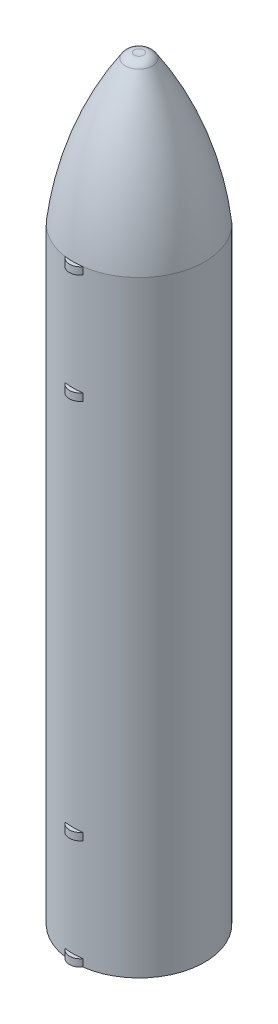
SolidWorks part; units mm, degrees
ref_plane "Front Plane" through (0, 0, 0) normal (0, 0, 1) x (1, 0, 0)
ref_plane "Top Plane" through (0, 0, 0) normal (0, 1, 0) x (1, 0, 0)
ref_plane "Right Plane" through (0, 0, 0) normal (1, 0, 0) x (0, 0, -1)
sketch "Sketch1" plane through (0, 0, 0) normal (0, 1, 0) x (1, 0, 0)
  circle A0 centre (0, 0) radius 4500
  dimension "D1" = 9000
extrude "Boss-Extrude1" add sketch "Sketch1" along normal blind 41600
sketch "Sketch2" plane through (0, 0, 0) normal (0, 0, 1) x (1, 0, 0)
  line L0 (0, 51786.1861) -> (0, 41600)
  line L1 (4500, 41600) -> (-4500, 41600) construction
  line L3 (0, 51786.1861) -> (317.0703, 51786.1861)
  line L4 (0, 41600) -> (4500, 41600)
  arc A1 (317.0703, 51786.1861) -> (930.3579, 51456.5597) centre (317.0703, 51050.8455) cw
  arc A2 (930.3579, 51456.5597) -> (4500, 41600) centre (-17690.3081, 39138.2485) cw
  point P5 (930.3579, 51456.5597)
  dimension "D1" = 22326.4416
  dimension "D3" = 735.3405
  dimension "D2" = 9856.5597
  dimension "D4" = 317.0703
revolve "Revolve1" add sketch "Sketch2" angle 360 about L0
sketch "Sketch4" plane through (0, 0, 0) normal (0, -1, 0) x (1, 0, 0)
  line L0 (2032.7129, 0) -> (-2032.7129, 0) construction
  arc A0 (-607.2547, -4458.8386) -> (607.2547, -4458.8386) centre (0, -4018.6776) ccw
  circle A1 centre (0, 0) radius 4500 construction
  arc A2 (-607.2547, 4458.8386) -> (607.2547, 4458.8386) centre (0, 4018.6776) cw
  arc A3 (-607.2547, -4458.8386) -> (607.2547, -4458.8386) centre (0, 0) ccw
  arc A4 (607.2547, 4458.8386) -> (-607.2547, 4458.8386) centre (0, 0) ccw
  point P10 (0, 0)
  point P12 (0, 0)
  dimension "D1" = 750
  dimension "D2" = 4458.8386
extrude "Boss-Extrude3" add sketch "Sketch4" against normal blind 500 contours A2 A4 | A0 A3
pattern_linear "LPattern1" count 2 spacing 7500 along (0, 1, 0) of "Boss-Extrude3"
ref_plane "Plane1" through (0, 20800, 0) normal (0, -1, 0) x (-1, 0, 0)
mirror "Mirror1" about plane through (0, 20800, 0) normal (0, -1, 0) of "LPattern1", "Boss-Extrude3"
